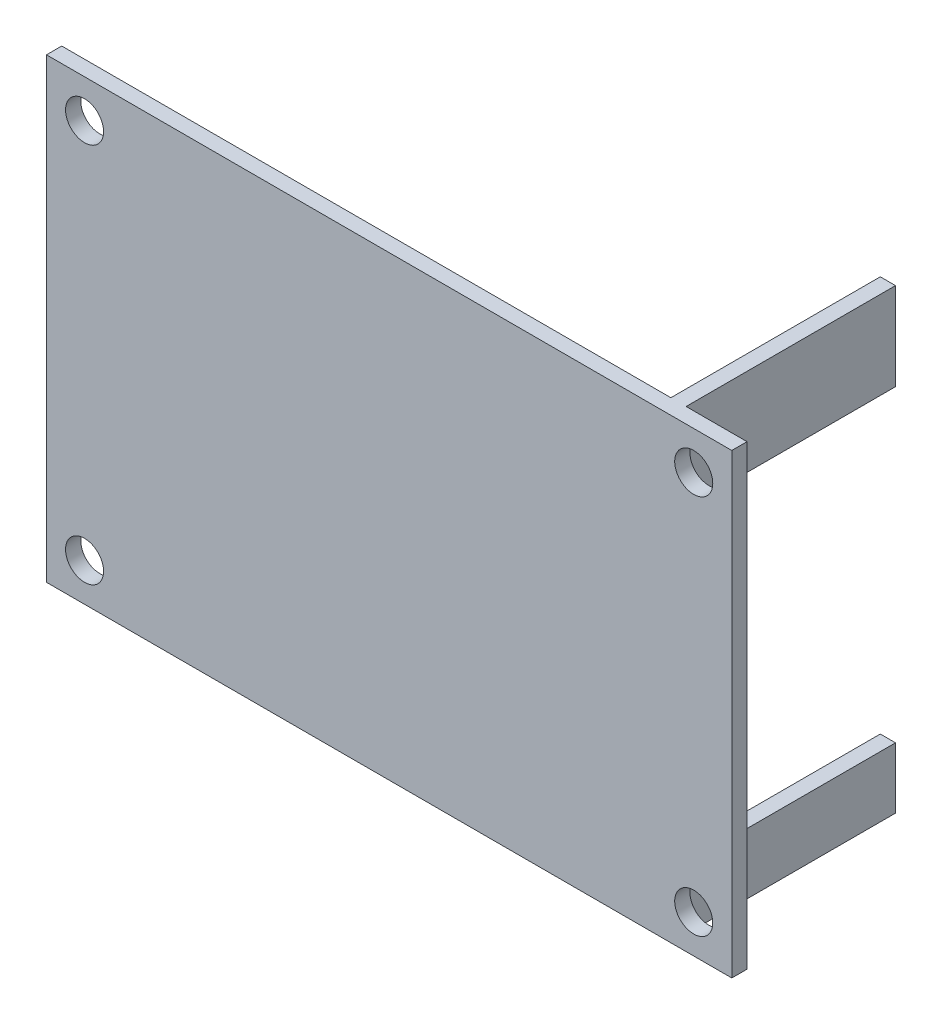
SolidWorks part; units mm, degrees
material "AISI 1020"
ref_plane "Front Plane" through (0, 0, 0) normal (0, 0, 1) x (1, 0, 0)
ref_plane "Top Plane" through (0, 0, 0) normal (0, 1, 0) x (1, 0, 0)
ref_plane "Right Plane" through (0, 0, 0) normal (1, 0, 0) x (0, 0, -1)
sketch "Sketch1" plane through (0, 0, 0) normal (0, 0, 1) x (1, 0, 0)
  line L1 (-45, -30) -> (45, -30)
  line L2 (-45, -30) -> (-45, 30)
  line L3 (-45, 30) -> (45, 30)
  line L4 (45, -30) -> (45, 30)
  line L5 (-45, -30) -> (45, 30) construction
  line L6 (-45, 30) -> (45, -30) construction
  point P0 (0, 0)
  dimension "D1" = 60
  dimension "D2" = 90
extrude "Boss-Extrude1" add sketch "Sketch1" along normal blind 2
sketch "Sketch2" plane through (0, 0, 2) normal (0, 0, 1) x (1, 0, 0)
  line L0 (-45, -30) -> (45, -30) construction
  line L1 (-45, 30) -> (-45, -30) construction
  line L2 (45, 30) -> (-45, 30) construction
  line L3 (45, -30) -> (45, 30) construction
  line L4 (45, -30) -> (45, 30) construction
  circle A0 centre (-40, -25) radius 2.5
  circle A1 centre (-40, 25) radius 2.5
  circle A2 centre (40, 25) radius 2.5
  circle A3 centre (40, -25) radius 2.5
  dimension "D1" = 5
  dimension "D4" = 5
  dimension "D5" = 5
  dimension "D6" = 5
  dimension "D2" = 5
  dimension "D3" = 5
  dimension "D7" = 5
  dimension "D8" = 5
  dimension "D9" = 5
  dimension "D10" = 5
  dimension "D11" = 5
  dimension "D12" = 5
extrude "Cut-Extrude1" cut sketch "Sketch2" against normal blind 10
sketch "Sketch3" plane through (0, 0, 0) normal (0, 0, -1) x (-1, 0, 0)
  line L11 (-45, -30) -> (-37, -30) construction
  line L12 (45, -30) -> (-45, -30) construction
  line L13 (-45, 30) -> (45, 30) construction
  line L14 (-37, -30) -> (-35, -30)
  line L15 (-37, -30) -> (-37, 30)
  line L16 (-37, 30) -> (-35, 30)
  line L17 (-35, -30) -> (-35, 30)
  line L18 (-37, -30) -> (-35, 30) construction
  line L19 (-37, 30) -> (-35, -30) construction
  point P9 (-36, 0)
  dimension "D1" = 8
  dimension "D2" = 2
extrude "Boss-Extrude4" add sketch "Sketch3" along normal blind 27.5
sketch "Sketch4" plane through (37, 0, 0) normal (1, 0, 0) x (0, 0, -1)
  line L0 (27.5, 30) -> (27.5, -30) construction
  line L1 (27.5, 18.5) -> (7.5, 18.5)
  line L2 (27.5, 18.5) -> (27.5, -22)
  line L3 (27.5, -22) -> (7.5, -22)
  line L4 (7.5, 18.5) -> (7.5, -22)
  line L5 (27.5, 18.5) -> (7.5, -22) construction
  line L6 (27.5, -22) -> (7.5, 18.5) construction
  line L8 (27.5, -30) -> (0, -30) construction
  line L9 (27.5, 30) -> (0, 30) construction
  point P4 (17.5, -1.75)
  dimension "D1" = 8
  dimension "D2" = 20
  dimension "D3" = 11.5
extrude "Cut-Extrude2" cut sketch "Sketch4" against normal blind 10
